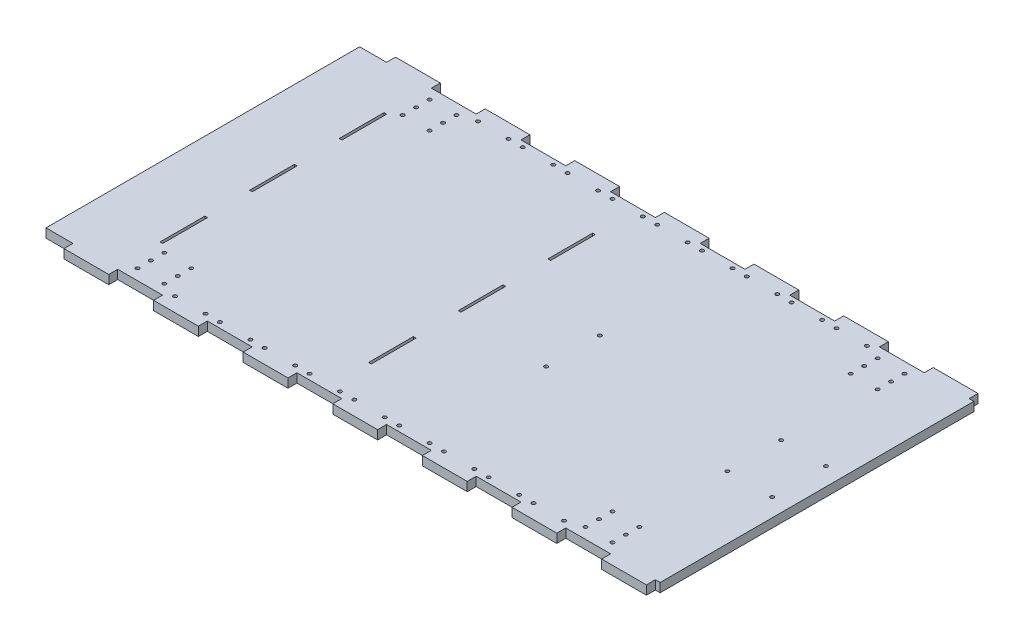
SolidWorks part; units mm, degrees
material "아크릴(내충격성)"
ref_plane "정면" through (0, 0, 0) normal (0, 0, 1) x (1, 0, 0)
ref_plane "윗면" through (0, 0, 0) normal (0, 1, 0) x (1, 0, 0)
ref_plane "우측면" through (0, 0, 0) normal (1, 0, 0) x (0, 0, -1)
sketch "스케치1" plane through (0, 0, 0) normal (0, 1, 0) x (1, 0, 0)
  line L0 (-359.4325, 185) -> (468.9528, 185) construction
  line L1 (-478.2031, 175) -> (-448.1731, 175)
  line L4 (207.1569, 175) -> (207.1569, -175)
  line L5 (-371.3643, -165.9489) -> (484.4188, -165.9489) construction
  line L6 (-412.6068, 0) -> (554.8748, 0) construction
  line L7 (-448.1731, 175) -> (-448.1731, 185)
  line L8 (-448.1731, 185) -> (-398.1731, 185)
  line L9 (-398.1731, 185) -> (-398.1731, 175)
  line L10 (-348.1731, 185) -> (-298.1731, 185)
  line L11 (-348.1731, 175) -> (-348.1731, 185)
  line L12 (-298.1731, 185) -> (-298.1731, 175)
  line L13 (-248.1731, 185) -> (-198.1731, 185)
  line L14 (-248.1731, 175) -> (-248.1731, 185)
  line L15 (-198.1731, 185) -> (-198.1731, 175)
  line L16 (-148.1731, 185) -> (-98.1731, 185)
  line L17 (-148.1731, 175) -> (-148.1731, 185)
  line L18 (-98.1731, 185) -> (-98.1731, 175)
  line L19 (-48.1731, 185) -> (1.8269, 185)
  line L20 (-48.1731, 175) -> (-48.1731, 185)
  line L21 (1.8269, 185) -> (1.8269, 175)
  line L22 (51.8269, 185) -> (101.8269, 185)
  line L23 (51.8269, 175) -> (51.8269, 185)
  line L24 (101.8269, 185) -> (101.8269, 175)
  line L25 (151.8269, 185) -> (201.8269, 185)
  line L26 (151.8269, 175) -> (151.8269, 185)
  line L27 (201.8269, 185) -> (201.8269, 175)
  line L28 (-398.1731, 175) -> (-348.1731, 175)
  line L29 (-298.1731, 175) -> (-248.1731, 175)
  line L30 (-198.1731, 175) -> (-148.1731, 175)
  line L31 (-98.1731, 175) -> (-48.1731, 175)
  line L32 (101.8269, 175) -> (151.8269, 175)
  line L33 (201.8269, 175) -> (207.1569, 175)
  line L34 (1.8269, 175) -> (51.8269, 175)
  line L35 (1.8269, -175) -> (51.8269, -175)
  line L36 (201.8269, -175) -> (207.1569, -175)
  line L37 (101.8269, -175) -> (151.8269, -175)
  line L38 (-98.1731, -175) -> (-48.1731, -175)
  line L39 (-198.1731, -175) -> (-148.1731, -175)
  line L40 (-298.1731, -175) -> (-248.1731, -175)
  line L41 (-398.1731, -175) -> (-348.1731, -175)
  line L42 (201.8269, -185) -> (201.8269, -175)
  line L43 (151.8269, -175) -> (151.8269, -185)
  line L44 (151.8269, -185) -> (201.8269, -185)
  line L45 (101.8269, -185) -> (101.8269, -175)
  line L46 (51.8269, -175) -> (51.8269, -185)
  line L47 (51.8269, -185) -> (101.8269, -185)
  line L48 (1.8269, -185) -> (1.8269, -175)
  line L49 (-48.1731, -175) -> (-48.1731, -185)
  line L50 (-48.1731, -185) -> (1.8269, -185)
  line L51 (-98.1731, -185) -> (-98.1731, -175)
  line L52 (-148.1731, -175) -> (-148.1731, -185)
  line L53 (-148.1731, -185) -> (-98.1731, -185)
  line L54 (-198.1731, -185) -> (-198.1731, -175)
  line L55 (-248.1731, -175) -> (-248.1731, -185)
  line L56 (-248.1731, -185) -> (-198.1731, -185)
  line L57 (-298.1731, -185) -> (-298.1731, -175)
  line L58 (-348.1731, -175) -> (-348.1731, -185)
  line L59 (-348.1731, -185) -> (-298.1731, -185)
  line L60 (-398.1731, -185) -> (-398.1731, -175)
  line L61 (-448.1731, -185) -> (-398.1731, -185)
  line L62 (-448.1731, -175) -> (-448.1731, -185)
  line L63 (-478.2031, -175) -> (-448.1731, -175)
  line L64 (-491.2031, 169) -> (207.1569, 169) construction
  line L65 (-388.1731, -175) -> (-388.1731, -88.8587) construction
  line L66 (-358.1731, -175) -> (-358.1731, -114.6349) construction
  line L67 (-388.1731, -163) -> (-388.1731, -148) construction
  line L68 (111.8269, -175) -> (111.8269, -128.5654) construction
  line L69 (141.8269, -175) -> (141.8269, -126.4818) construction
  line L70 (-168.1731, 175) -> (-168.1731, -175) construction
  line L72 (-168.1731, 125) -> (-165.1731, 125)
  line L73 (-168.1731, 125) -> (-168.1731, 75)
  line L74 (-168.1731, 75) -> (-165.1731, 75)
  line L75 (-165.1731, 125) -> (-165.1731, 75)
  line L76 (-168.1731, 25) -> (-165.1731, 25)
  line L77 (-168.1731, 25) -> (-168.1731, -25)
  line L78 (-168.1731, -25) -> (-165.1731, -25)
  line L79 (-165.1731, 25) -> (-165.1731, -25)
  line L80 (-168.1731, -75) -> (-165.1731, -75)
  line L81 (-168.1731, -75) -> (-168.1731, -125)
  line L82 (-168.1731, -125) -> (-165.1731, -125)
  line L83 (-165.1731, -75) -> (-165.1731, -125)
  line L98 (-400.9731, 185) -> (-400.9731, -185) construction
  line L99 (-478.2031, -175) -> (-478.2031, 175)
  line L100 (-400.9731, 125) -> (-397.9731, 125)
  line L101 (-400.9731, 125) -> (-400.9731, 75)
  line L102 (-400.9731, 75) -> (-397.9731, 75)
  line L103 (-397.9731, 125) -> (-397.9731, 75)
  line L104 (-400.9731, 25) -> (-397.9731, 25)
  line L105 (-400.9731, 25) -> (-400.9731, -25)
  line L106 (-400.9731, -25) -> (-397.9731, -25)
  line L107 (-397.9731, 25) -> (-397.9731, -25)
  line L108 (-400.9731, -75) -> (-397.9731, -75)
  line L109 (-400.9731, -75) -> (-400.9731, -125)
  line L110 (-400.9731, -125) -> (-397.9731, -125)
  line L111 (-397.9731, -75) -> (-397.9731, -125)
  circle A2 centre (-340.1731, 169) radius 2
  circle A3 centre (-306.1731, 169) radius 2
  circle A4 centre (-290.1731, 169) radius 2
  circle A5 centre (-256.1731, 169) radius 2
  circle A6 centre (-240.1731, 169) radius 2
  circle A7 centre (-206.1731, 169) radius 2
  circle A8 centre (-190.1731, 169) radius 2
  circle A9 centre (-156.1731, 169) radius 2
  circle A10 centre (-140.1731, 169) radius 2
  circle A11 centre (-106.1731, 169) radius 2
  circle A12 centre (-90.1731, 169) radius 2
  circle A13 centre (-56.1731, 169) radius 2
  circle A14 centre (-40.1731, 169) radius 2
  circle A15 centre (-6.1731, 169) radius 2
  circle A16 centre (9.8269, 169) radius 2
  circle A17 centre (43.8269, 169) radius 2
  circle A18 centre (59.8269, 169) radius 2
  circle A19 centre (93.8269, 169) radius 2
  circle A24 centre (93.8269, -169) radius 2
  circle A25 centre (59.8269, -169) radius 2
  circle A26 centre (43.8269, -169) radius 2
  circle A27 centre (9.8269, -169) radius 2
  circle A28 centre (-6.1731, -169) radius 2
  circle A29 centre (-40.1731, -169) radius 2
  circle A30 centre (-56.1731, -169) radius 2
  circle A31 centre (-90.1731, -169) radius 2
  circle A32 centre (-106.1731, -169) radius 2
  circle A33 centre (-140.1731, -169) radius 2
  circle A34 centre (-156.1731, -169) radius 2
  circle A35 centre (-190.1731, -169) radius 2
  circle A36 centre (-206.1731, -169) radius 2
  circle A37 centre (-240.1731, -169) radius 2
  circle A38 centre (-256.1731, -169) radius 2
  circle A39 centre (-290.1731, -169) radius 2
  circle A40 centre (-306.1731, -169) radius 2
  circle A41 centre (-340.1731, -169) radius 2
  circle A44 centre (-388.1731, -163) radius 2
  circle A45 centre (-358.1731, -163) radius 2
  circle A46 centre (-388.1731, -148) radius 2
  circle A47 centre (-358.1731, -148) radius 2
  circle A48 centre (-388.1731, -133) radius 2
  circle A49 centre (-358.1731, -133) radius 2
  circle A50 centre (-358.1731, 163) radius 2
  circle A51 centre (-388.1731, 163) radius 2
  circle A52 centre (-388.1731, 148) radius 2
  circle A53 centre (-358.1731, 148) radius 2
  circle A54 centre (-358.1731, 133) radius 2
  circle A55 centre (-388.1731, 133) radius 2
  circle A58 centre (111.8269, -163) radius 2
  circle A59 centre (141.8269, -163) radius 2
  circle A60 centre (111.8269, -148) radius 2
  circle A61 centre (141.8269, -148) radius 2
  circle A62 centre (111.8269, -133) radius 2
  circle A63 centre (141.8269, -133) radius 2
  circle A64 centre (141.8269, 133) radius 2
  circle A65 centre (141.8269, 148) radius 2
  circle A66 centre (141.8269, 163) radius 2
  circle A67 centre (111.8269, 163) radius 2
  circle A68 centre (111.8269, 148) radius 2
  circle A69 centre (111.8269, 133) radius 2
  point P68 (207.1569, 0)
  point P69 (-498.1731, 0)
  dimension "D2" = 10
  dimension "D12" = 12
  dimension "D1" = 6
  dimension "D3" = 10
  dimension "D4" = 50
  dimension "D7" = 175
  dimension "D8" = 10
  dimension "D10" = 10
  dimension "D11" = 10
  dimension "D13" = 12
  dimension "D15" = 15
  dimension "D9" = 12
  dimension "D16" = 12
  dimension "D18" = 30.03
  dimension "D19" = 3
  dimension "D20" = 3
  dimension "D21" = 3
  dimension "D22" = 50
  dimension "D23" = 50
  dimension "D24" = 50
  dimension "D25" = 50
  dimension "D26" = 50
  dimension "D27" = 50
  dimension "D32" = 3
  dimension "D33" = 3
  dimension "D34" = 3
  dimension "D35" = 30
  dimension "D6" = 7
  dimension "D14" = 3
  dimension "D17" = 3
extrude "보스-돌출1" add sketch "스케치1" along normal blind 10
sketch "스케치2" plane through (0, 10, 0) normal (0, 1, 0) x (1, 0, 0)
  line L0 (207.1569, 0) -> (-209.7685, 0) construction
  line L1 (207.1569, -175) -> (207.1569, 175) construction
  line L2 (207.1569, 30) -> (-209.7685, 30) construction
  line L3 (-65.1731, 0) -> (-65.1731, 82.034) construction
  line L4 (-165.1731, -25) -> (-165.1731, 25) construction
  line L5 (187.1569, 76.1711) -> (187.1569, -43.2195) construction
  line L6 (137.1569, 76.1711) -> (137.1569, -43.2195) construction
  circle A1 centre (137.1569, 30) radius 2
  circle A2 centre (187.1569, 30) radius 2
  circle A3 centre (-65.1731, 30) radius 2
  circle A4 centre (-65.1731, -30) radius 2
  circle A5 centre (187.1569, -30) radius 2
  circle A6 centre (137.1569, -30) radius 2
  dimension "D1" = 30
  dimension "D2" = 100
  dimension "D3" = 202.33
  dimension "D4" = 50
extrude "컷-돌출1" cut sketch "스케치2" against normal through all
